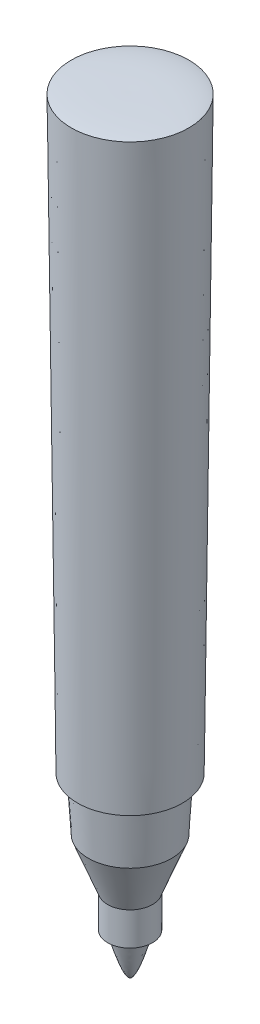
SolidWorks part; units mm, degrees
ref_plane "Front Plane" through (0, 0, 0) normal (0, 0, 1) x (1, 0, 0)
ref_plane "Top Plane" through (0, 0, 0) normal (0, 1, 0) x (1, 0, 0)
ref_plane "Right Plane" through (0, 0, 0) normal (1, 0, 0) x (0, 0, -1)
sketch "Sketch1" plane through (0, 0, 0) normal (0, 0, 1) x (1, 0, 0)
  line L0 (0, 0) -> (0, 130)
  line L1 (-9.95, 130) -> (9.95, 130) construction
  line L2 (-3.8, 7) -> (3.8, 7) construction
  line L3 (-3.8, 12.6) -> (3.8, 12.6) construction
  line L4 (-8.875, 30) -> (8.875, 30) construction
  line L5 (-7.05, 21) -> (7.05, 21) construction
  line L6 (-7.6, 30) -> (7.6, 30) construction
  line L7 (3.8, 7) -> (2.8, 7)
  line L8 (3.8, 7) -> (3.8, 12.6)
  line L9 (3.8, 12.6) -> (7.05, 21)
  line L10 (7.05, 21) -> (7.6, 30)
  line L11 (7.6, 30) -> (8.875, 30)
  line L12 (-9.95, 129.5) -> (9.95, 129.5) construction
  line L13 (8.875, 30) -> (9.95, 129.5)
  spline S0 degree 2 poles (0, 0) (0.935, 0.0329) (2.8, 7) knots 0 0 0 1 1 1
  spline S1 degree 2 poles (0, 130) (7.4447, 130.0874) (9.95, 129.5) knots 0 0 0 1 1 1
  point P6 (0, 130)
  point P9 (0, 7)
  point P12 (0, 12.6)
  point P15 (0, 30)
  point P18 (0, 21)
  point P22 (0, 30)
  point P25 (0, 129.5)
  dimension "D1" = 130
  dimension "D2" = 19.9
  dimension "D3" = 30
  dimension "D4" = 7
  dimension "D5" = 5.6
  dimension "D6" = 9
  dimension "D7" = 17.75
  dimension "D8" = 7.6
  dimension "D9" = 14.1
  dimension "D10" = 15.2
  dimension "D11" = 1
  dimension "D12" = 0.5
revolve "Revolve1" add sketch "Sketch1" angle 360 about L0
